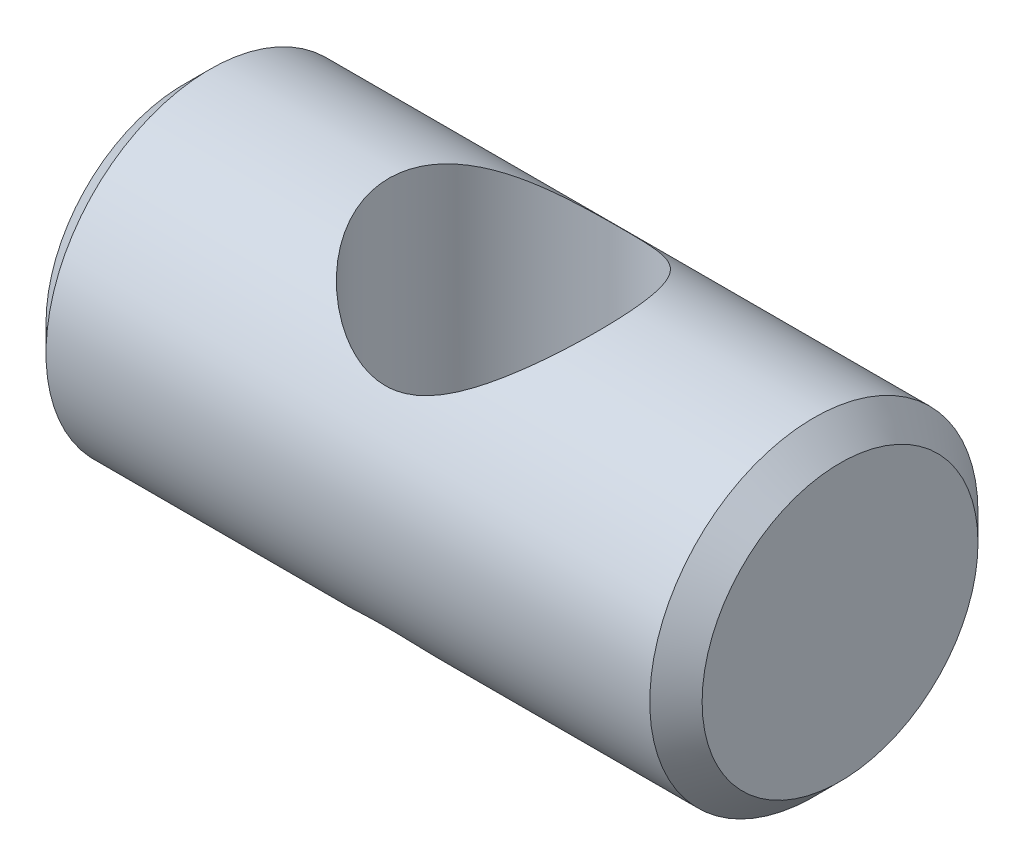
SolidWorks part; units mm, degrees
ref_plane "Front Plane" through (0, 0, 0) normal (0, 0, 1) x (1, 0, 0)
ref_plane "Top Plane" through (0, 0, 0) normal (0, 1, 0) x (1, 0, 0)
ref_plane "Right Plane" through (0, 0, 0) normal (1, 0, 0) x (0, 0, -1)
sketch "Sketch1" plane through (0, 0, 0) normal (1, 0, 0) x (0, 0, -1)
  circle A0 centre (0, 0) radius 4.765
  dimension "D1" = 9.53
extrude "Boss-Extrude1" add sketch "Sketch1" along normal mid plane 19.05
chamfer "Chamfer1" distance 0.76 angle 45 2 edges at (9.525, 0, -4.765) (-9.525, 0, -4.765)
sketch "Sketch2" plane through (0, 0, 0) normal (0, 1, 0) x (1, 0, 0)
  circle A0 centre (0, -0.25) radius 3.43
  dimension "D1" = 6.86
  dimension "D2" = 0.25
extrude "Cut-Extrude1" cut sketch "Sketch2" against normal through all both and the other way through all
